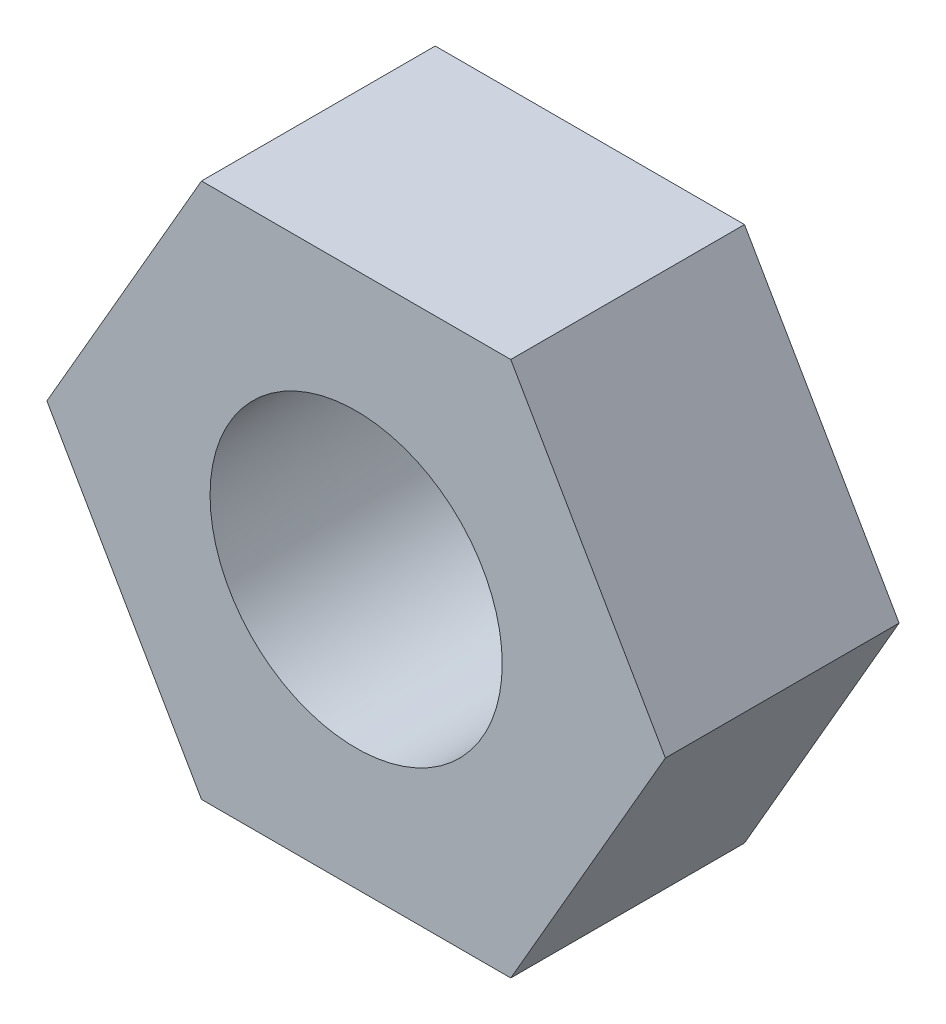
SolidWorks part; units mm, degrees
material "AISI 4340 Steel, normalized"
ref_plane "Front Plane" through (0, 0, 0) normal (0, 0, 1) x (1, 0, 0)
ref_plane "Top Plane" through (0, 0, 0) normal (0, 1, 0) x (1, 0, 0)
ref_plane "Right Plane" through (0, 0, 0) normal (1, 0, 0) x (0, 0, -1)
sketch "Sketch1" plane through (0, 0, 0) normal (0, 0, 1) x (1, 0, 0)
  line L0 (3.1754, 0) -> (1.5877, 2.75)
  line L1 (1.5877, 2.75) -> (-1.5877, 2.75)
  line L2 (-1.5877, 2.75) -> (-3.1754, 0)
  line L3 (-3.1754, 0) -> (-1.5877, -2.75)
  line L4 (-1.5877, -2.75) -> (1.5877, -2.75)
  line L5 (1.5877, -2.75) -> (3.1754, 0)
  circle A0 centre (0, 0) radius 1.5
extrude "Nut" add sketch "Sketch1" along normal blind 2.4
